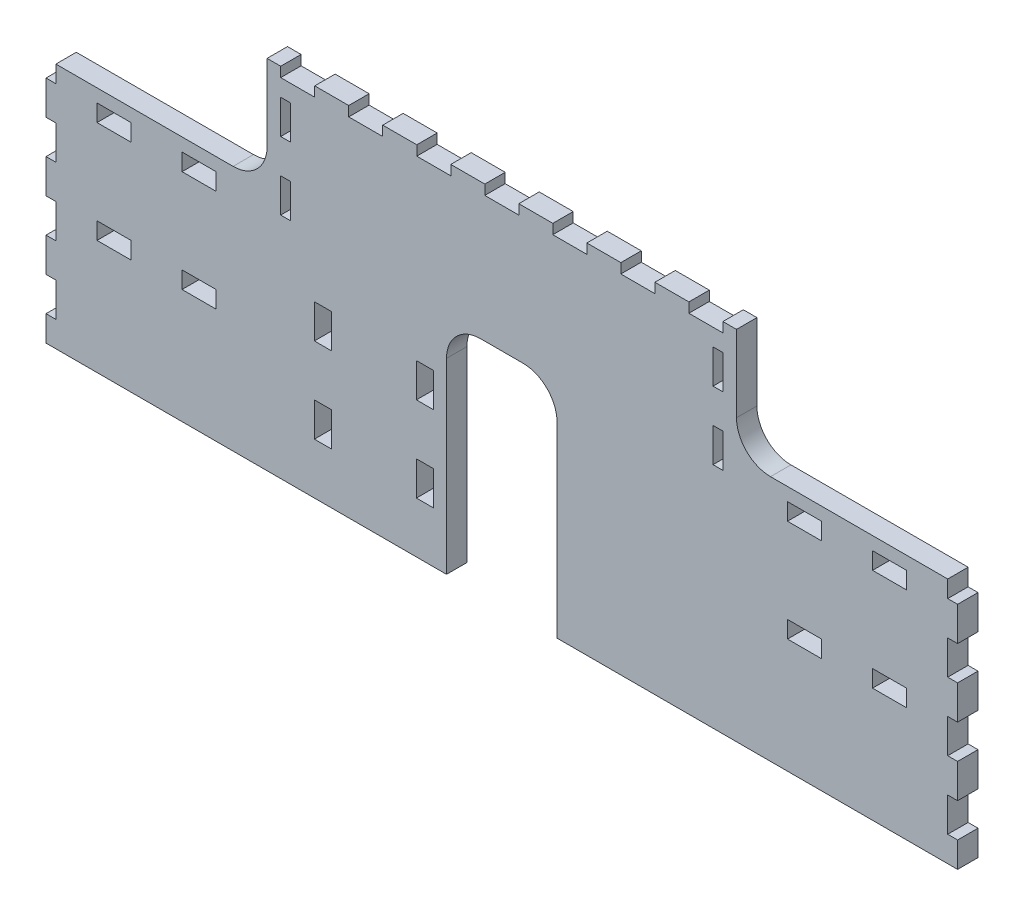
SolidWorks part; units mm, degrees
material "Pine"
ref_plane "Front Plane" through (0, 0, 0) normal (0, 0, 1) x (1, 0, 0)
ref_plane "Top Plane" through (0, 0, 0) normal (0, 1, 0) x (1, 0, 0)
ref_plane "Right Plane" through (0, 0, 0) normal (1, 0, 0) x (0, 0, -1)
sketch "Sketch1" plane through (0, 0, 0) normal (0, 0, 1) x (1, 0, 0)
  line L1 (134, -65) -> (16.25, -65)
  line L2 (134, -65) -> (134, 7.5)
  line L3 (134, 7.5) -> (69, 7.5)
  line L4 (-134, -65) -> (-134, 7.5)
  line L5 (0, 0) -> (0, 40) construction
  line L7 (16.25, -65) -> (16.25, 0)
  line L8 (16.25, 0) -> (-16.25, 0)
  line L9 (-16.25, -65) -> (-16.25, 0)
  line L12 (69, 7.5) -> (69, 40)
  line L13 (69, 40) -> (-69, 40)
  line L14 (-69, 7.5) -> (-69, 40)
  line L15 (-16.25, -65) -> (-134, -65)
  line L16 (-69, 7.5) -> (-134, 7.5)
  dimension "D1" = 65
  dimension "D2" = 138
  dimension "D3" = 72.5
  dimension "D4" = 32.5
  dimension "D5" = 117.75
extrude "Boss-Extrude1" add sketch "Sketch1" against normal blind 6
sketch "Sketch2" plane through (0, 0, 0) normal (0, 0, 1) x (1, 0, 0)
  line L0 (-109, -26.35) -> (-119, -26.35) construction
  line L1 (-109, -1.35) -> (-119, -1.35)
  line L2 (-109, -1.35) -> (-109, 3.65)
  line L3 (-109, 3.65) -> (-119, 3.65)
  line L4 (-119, -1.35) -> (-119, 3.65)
  line L5 (-109, -31.35) -> (-119, -31.35)
  line L6 (-109, -31.35) -> (-109, -26.35)
  line L7 (-109, -26.35) -> (-119, -26.35)
  line L8 (-119, -31.35) -> (-119, -26.35)
  line L10 (-94, -26.35) -> (-84, -26.35)
  line L11 (-94, -26.35) -> (-94, -31.35)
  line L12 (-94, -31.35) -> (-84, -31.35)
  line L13 (-84, -26.35) -> (-84, -31.35)
  line L15 (-94, 3.65) -> (-84, 3.65)
  line L16 (-94, 3.65) -> (-94, -1.35)
  line L17 (-94, -1.35) -> (-84, -1.35)
  line L18 (-84, 3.65) -> (-84, -1.35)
  line L20 (-55.1, -15) -> (-50.1, -15)
  line L21 (-55.1, -15) -> (-55.1, -25)
  line L22 (-55.1, -25) -> (-50.1, -25)
  line L23 (-50.1, -15) -> (-50.1, -25)
  line L24 (-50.1, -25) -> (-50.1, -15) construction
  line L26 (-25.1, -25) -> (-20.1, -25)
  line L27 (-25.1, -25) -> (-25.1, -15)
  line L28 (-25.1, -15) -> (-20.1, -15)
  line L29 (-20.1, -25) -> (-20.1, -15)
  line L31 (-50.1, -40) -> (-55.1, -40)
  line L32 (-50.1, -40) -> (-50.1, -50)
  line L33 (-50.1, -50) -> (-55.1, -50)
  line L34 (-55.1, -40) -> (-55.1, -50)
  line L35 (-25.1, -50) -> (-20.1, -50)
  line L36 (-25.1, -50) -> (-25.1, -40)
  line L37 (-25.1, -40) -> (-20.1, -40)
  line L38 (-20.1, -50) -> (-20.1, -40)
  line L39 (84, -26.35) -> (94, -26.35)
  line L40 (84, -26.35) -> (84, -31.35)
  line L41 (84, -31.35) -> (94, -31.35)
  line L42 (94, -26.35) -> (94, -31.35)
  line L43 (109, -31.35) -> (119, -31.35)
  line L44 (109, -31.35) -> (109, -26.35)
  line L45 (109, -26.35) -> (119, -26.35)
  line L46 (119, -31.35) -> (119, -26.35)
  line L47 (119, -1.35) -> (109, -1.35)
  line L48 (119, -1.35) -> (119, 3.65)
  line L49 (119, 3.65) -> (109, 3.65)
  line L50 (109, -1.35) -> (109, 3.65)
  line L51 (94, -1.35) -> (84, -1.35)
  line L52 (94, -1.35) -> (94, 3.65)
  line L53 (94, 3.65) -> (84, 3.65)
  line L54 (84, -1.35) -> (84, 3.65)
extrude "Cut-Extrude1" cut sketch "Sketch2" against normal through all both and the other way through all
fillet "Fillet1" radius 10 4 edges at (69, 7.5, -3) (16.25, 0, -3) (-16.25, 0, -3) (-69, 7.5, -3)
sketch "Sketch3" plane through (0, 0, -6) normal (0, 0, -1) x (-1, 0, 0)
  line L0 (-69, 40) -> (69, 40) construction
  line L1 (-5, 40) -> (5, 40)
  line L2 (-5, 40) -> (-5, 37.1)
  line L3 (-5, 37.1) -> (5, 37.1)
  line L4 (5, 40) -> (5, 37.1)
  line L5 (0, 37.1) -> (0, 0) construction
  line L6 (15, 40) -> (25, 40)
  line L7 (15, 40) -> (15, 37.1)
  line L8 (15, 37.1) -> (25, 37.1)
  line L9 (25, 40) -> (25, 37.1)
  line L10 (35, 40) -> (45, 40)
  line L11 (35, 40) -> (35, 37.1)
  line L12 (35, 37.1) -> (45, 37.1)
  line L13 (45, 40) -> (45, 37.1)
  line L14 (55, 40) -> (65, 40)
  line L15 (55, 40) -> (55, 37.1)
  line L16 (55, 37.1) -> (65, 37.1)
  line L17 (65, 40) -> (65, 37.1)
  line L18 (-5, 40) -> (15, 40) construction
  line L19 (-25, 40) -> (-15, 40)
  line L20 (-25, 40) -> (-25, 37.1)
  line L21 (-25, 37.1) -> (-15, 37.1)
  line L22 (-15, 40) -> (-15, 37.1)
  line L23 (-45, 40) -> (-35, 40)
  line L24 (-45, 40) -> (-45, 37.1)
  line L25 (-45, 37.1) -> (-35, 37.1)
  line L26 (-35, 40) -> (-35, 37.1)
  line L27 (-65, 40) -> (-55, 40)
  line L28 (-65, 40) -> (-65, 37.1)
  line L29 (-65, 37.1) -> (-55, 37.1)
  line L30 (-55, 40) -> (-55, 37.1)
  line L31 (-5, 40) -> (-25, 40) construction
  line L32 (-134, -7.5) -> (-131.1, -7.5)
  line L33 (-134, 12.5) -> (-131.1, 12.5)
  line L34 (-134, 12.5) -> (-134, 2.5)
  line L35 (-134, 2.5) -> (-131.1, 2.5)
  line L36 (-131.1, 12.5) -> (-131.1, 2.5)
  line L37 (-134, -7.5) -> (-134, -17.5)
  line L38 (-134, -17.5) -> (-131.1, -17.5)
  line L39 (-131.1, -7.5) -> (-131.1, -17.5)
  line L40 (-134, -27.5) -> (-131.1, -27.5)
  line L41 (-134, -27.5) -> (-134, -37.5)
  line L42 (-134, -37.5) -> (-131.1, -37.5)
  line L43 (-131.1, -27.5) -> (-131.1, -37.5)
  line L44 (-134, -47.5) -> (-131.1, -47.5)
  line L45 (-134, -47.5) -> (-134, -57.5)
  line L46 (-134, -57.5) -> (-131.1, -57.5)
  line L47 (-131.1, -47.5) -> (-131.1, -57.5)
  line L48 (131.1, -47.5) -> (131.1, -57.5)
  line L49 (134, -57.5) -> (131.1, -57.5)
  line L50 (134, -47.5) -> (134, -57.5)
  line L51 (134, -47.5) -> (131.1, -47.5)
  line L52 (131.1, -27.5) -> (131.1, -37.5)
  line L53 (134, -37.5) -> (131.1, -37.5)
  line L54 (134, -27.5) -> (134, -37.5)
  line L55 (134, -27.5) -> (131.1, -27.5)
  line L56 (131.1, -7.5) -> (131.1, -17.5)
  line L57 (134, -17.5) -> (131.1, -17.5)
  line L58 (134, -7.5) -> (134, -17.5)
  line L59 (131.1, 12.5) -> (131.1, 2.5)
  line L60 (134, 2.5) -> (131.1, 2.5)
  line L61 (134, 12.5) -> (134, 2.5)
  line L62 (134, 12.5) -> (131.1, 12.5)
  line L63 (134, -7.5) -> (131.1, -7.5)
  line L64 (-134, 7.5) -> (-79, 7.5) construction
  line L65 (-134, -65) -> (-134, 7.5) construction
  dimension "D1" = 10
  dimension "D2" = 2.9
  dimension "D3" = 4
  dimension "D4" = 20
  dimension "D6" = 20
  dimension "D7" = 2.9
  dimension "D8" = 10
  dimension "D10" = 10
  dimension "D11" = 5
  dimension "D5" = 4
  dimension "D9" = 4
extrude "Cut-Extrude2" cut sketch "Sketch3" against normal through all both and the other way through all
sketch "Sketch4" plane through (0, 0, -6) normal (0, 0, -1) x (-1, 0, 0)
  line L0 (65, 37.1) -> (55, 37.1) construction
  line L1 (65, 32.1) -> (62.1, 32.1)
  line L2 (65, 32.1) -> (65, 22.1)
  line L3 (65, 22.1) -> (62.1, 22.1)
  line L4 (62.1, 32.1) -> (62.1, 22.1)
  line L5 (65, 12.1) -> (62.1, 12.1)
  line L6 (65, 12.1) -> (65, 2.1)
  line L7 (65, 2.1) -> (62.1, 2.1)
  line L8 (62.1, 12.1) -> (62.1, 2.1)
  line L9 (65, 32.1) -> (65, 12.1) construction
  line L10 (0, 0) -> (0, 40.1) construction
  line L11 (6.25, 0) -> (-6.25, 0) construction
  line L12 (134.1, 40.1) -> (-134.1, 40.1) construction
  line L13 (-65, 32.1) -> (-65, 12.1) construction
  line L14 (-62.1, 12.1) -> (-62.1, 2.1)
  line L15 (-65, 2.1) -> (-62.1, 2.1)
  line L16 (-65, 12.1) -> (-65, 2.1)
  line L17 (-65, 12.1) -> (-62.1, 12.1)
  line L18 (-62.1, 32.1) -> (-62.1, 22.1)
  line L19 (-65, 22.1) -> (-62.1, 22.1)
  line L20 (-65, 32.1) -> (-65, 22.1)
  line L21 (-65, 32.1) -> (-62.1, 32.1)
  dimension "D1" = 10
  dimension "D2" = 5
  dimension "D3" = 2.9
  dimension "D5" = 20
  dimension "D4" = 2
extrude "Cut-Extrude3" cut sketch "Sketch4" against normal through all
